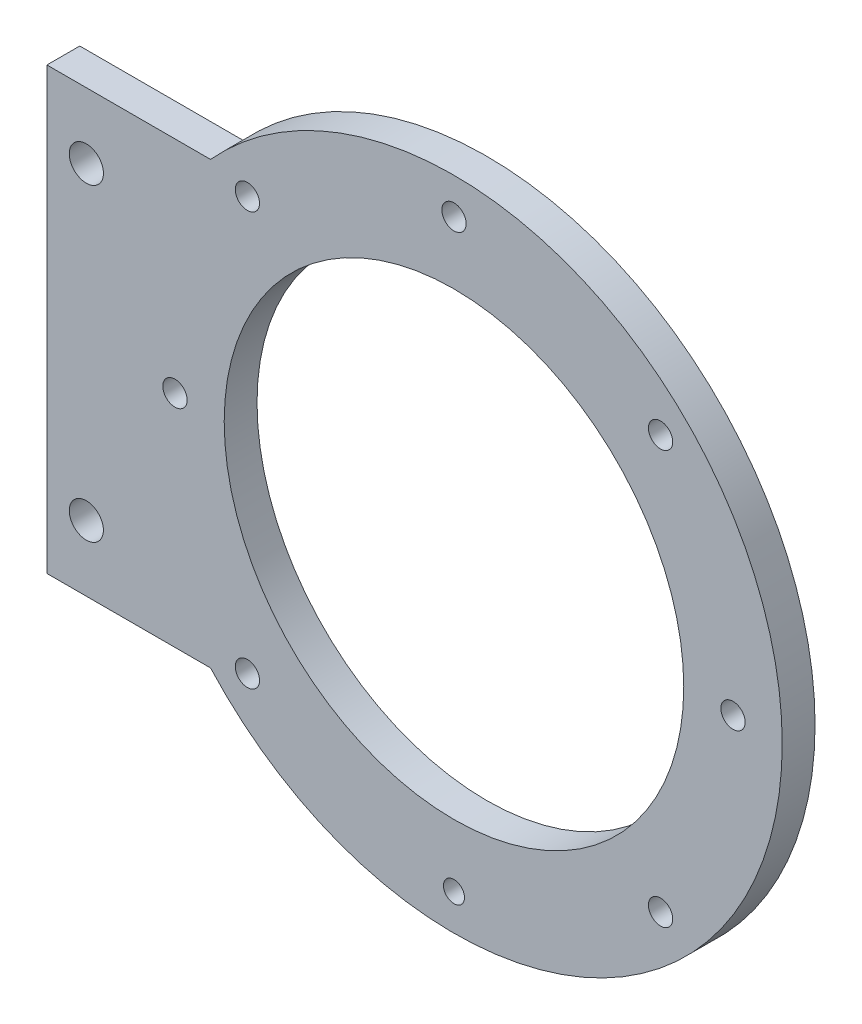
SolidWorks part; units mm, degrees
ref_plane "前视基准面" through (0, 0, 0) normal (0, 0, 1) x (1, 0, 0)
ref_plane "上视基准面" through (0, 0, 0) normal (0, 1, 0) x (1, 0, 0)
ref_plane "右视基准面" through (0, 0, 0) normal (1, 0, 0) x (0, 0, -1)
other "Configuration Table"
sketch "草图1" plane through (0, 0, 0) normal (0, 0, 1) x (1, 0, 0)
  line L0 (0, -67.082) -> (0, 0)
  line L1 (0, -67.082) -> (-12, -67.082)
  line L2 (-12, -67.082) -> (-12, 0)
  line L3 (0, 0) -> (-12, 0)
  line L4 (-12, -33.541) -> (95.5454, -33.541) construction
  line L5 (0, 0) -> (20, 0)
  line L6 (0, 0) -> (0, -67.082)
  line L7 (0, -67.082) -> (20, -67.082)
  line L8 (20, 0) -> (20, -67.082)
  circle A0 centre (-6, -57.082) radius 2.6
  circle A1 centre (-6, -10) radius 2.6
  circle A2 centre (50, -33.541) radius 50
  dimension "D1" = 5.2
  dimension "D2" = 6
  dimension "D5" = 6
  dimension "D6" = 10
  dimension "D8" = 6
  dimension "D9" = 5.2
  dimension "D10" = 10
  dimension "D12" = 100
  dimension "D3" = 12
  dimension "D4" = 67.082
  dimension "D7" = 12
  dimension "D11" = 20
  dimension "D13" = 50
extrude "凸台-拉伸1" add sketch "草图1" along normal blind 5
sketch "草图2" plane through (0, 0, 5) normal (0, 0, 1) x (1, 0, 0)
  line L3 (12.919, 0) -> (-12, 0)
  line L4 (-12, 0) -> (-12, -67.082)
  line L5 (-12, -67.082) -> (12.919, -67.082)
  line L6 (12.919, 0) -> (-12, 0)
  line L7 (-12, 0) -> (-12, -67.082)
  line L8 (-12, -67.082) -> (12.919, -67.082)
  arc A1 (12.919, -67.082) -> (12.919, 0) centre (50, -33.541) ccw
  arc A2 (12.919, -67.082) -> (12.919, 0) centre (50, -33.541) ccw
  circle A5 centre (92.5, -33.541) radius 1.85
  circle A16 centre (80.052, -63.5931) radius 1.85
  circle A17 centre (50, -76.041) radius 1.85
  circle A18 centre (19.948, -63.5931) radius 1.85
  circle A19 centre (7.5, -33.541) radius 1.85
  circle A20 centre (19.948, -3.489) radius 1.85
  circle A21 centre (50, 8.959) radius 1.85
  circle A22 centre (80.052, -3.489) radius 1.85
  point P18 (50, -33.541)
  point P25 (50, -33.541)
  dimension "D2" = 8
  dimension "D6" = 3.7
  dimension "D5" = 42.5
  dimension "D1" = 0
extrude "切除-拉伸1" cut sketch "草图2" against normal through all
sketch "草图3" plane through (0, 0, 5) normal (0, 0, 1) x (1, 0, 0)
  line L3 (12.919, 0) -> (-12, 0)
  line L4 (-12, 0) -> (-12, -67.082)
  line L5 (-12, -67.082) -> (12.919, -67.082)
  line L6 (12.919, 0) -> (-12, 0)
  line L7 (-12, 0) -> (-12, -67.082)
  line L8 (-12, -67.082) -> (12.919, -67.082)
  circle A0 centre (50, -33.541) radius 35
  arc A1 (12.919, -67.082) -> (12.919, 0) centre (50, -33.541) ccw
  arc A2 (12.919, -67.082) -> (12.919, 0) centre (50, -33.541) ccw
  dimension "D2" = 70
  dimension "D1" = 0
extrude "切除-拉伸2" cut sketch "草图3" against normal through all contours A0
sketch "草图4" plane through (0, 0, 5) normal (0, 0, 1) x (1, 0, 0)
  line L3 (12.919, 0) -> (-12, 0)
  line L4 (-12, 0) -> (-12, -67.082)
  line L5 (-12, -67.082) -> (12.919, -67.082)
  line L6 (12.919, 0) -> (-12, 0)
  line L7 (-12, 0) -> (-12, -67.082)
  line L8 (-12, -67.082) -> (12.919, -67.082)
  circle A0 centre (50, 10.959) radius 1.85
  arc A1 (12.919, -67.082) -> (12.919, 0) centre (50, -33.541) ccw
  arc A2 (12.919, -67.082) -> (12.919, 0) centre (50, -33.541) ccw
  circle A3 centre (81.4663, -2.0748) radius 1.85
  circle A4 centre (50, -78.041) radius 1.6
  circle A5 centre (94.5, -33.541) radius 1.85
  circle A6 centre (81.4663, -65.0073) radius 1.85
  circle A7 centre (50, -78.041) radius 1.85
  circle A8 centre (18.5337, -65.0073) radius 1.85
  circle A9 centre (5.5, -33.541) radius 1.85
  circle A10 centre (18.5337, -2.0748) radius 1.85
  point P26 (50, -33.541)
  point P28 (50, -33.541)
  dimension "D2" = 3.7
  dimension "D4" = 3.2
  dimension "D5" = 44.5
  dimension "D3" = 44.5
  dimension "D1" = 0
  dimension "D6" = 8
extrude "切除-拉伸3" cut sketch "草图4" against normal blind 10 contours A0 | A4 | A10 | A3 | A8 | A6
sketch "草图5" plane through (0, 0, 5) normal (0, 0, 1) x (1, 0, 0)
  circle A1 centre (-6, -10) radius 2.6
  circle A2 centre (-6, -10) radius 2.6
  circle A3 centre (-6, -57.082) radius 2.6
  circle A4 centre (-6, -57.082) radius 2.6
  circle A5 centre (7.5, -33.541) radius 1.85
  circle A6 centre (7.5, -33.541) radius 1.85
  circle A7 centre (92.5, -33.541) radius 1.85
  circle A8 centre (92.5, -33.541) radius 1.85
  circle A9 centre (50, -33.541) radius 35
  circle A10 centre (50, -33.541) radius 35
  circle A11 centre (18.5337, -65.0073) radius 1.85
  circle A12 centre (18.5337, -65.0073) radius 1.85
  circle A13 centre (81.4663, -2.0748) radius 1.85
  circle A14 centre (81.4663, -2.0748) radius 1.85
  circle A15 centre (18.5337, -2.0748) radius 1.85
  circle A16 centre (18.5337, -2.0748) radius 1.85
  circle A17 centre (50, -78.041) radius 1.6
  circle A18 centre (50, -78.041) radius 1.6
  circle A19 centre (81.4663, -65.0073) radius 1.85
  circle A20 centre (81.4663, -65.0073) radius 1.85
  circle A21 centre (50, 10.959) radius 1.85
  circle A22 centre (50, 10.959) radius 1.85
  dimension "D1" = 0
  dimension "D2" = 0
  dimension "D3" = 0
  dimension "D4" = 0
  dimension "D5" = 0
  dimension "D6" = 0
  dimension "D7" = 0
  dimension "D8" = 0
  dimension "D9" = 0
  dimension "D10" = 0
  dimension "D11" = 0
move or copy body "实体-移动/复制1" [suppressed] bodies to move or copy 109 parameters "D1"=0, "D2"=0, "D3"=0
move or copy body "实体-移动/复制2" [suppressed] bodies to move or copy 110 parameters "D1"=0, "D2"=0, "D3"=0
move or copy body "实体-移动/复制3" [suppressed] bodies to move or copy 111 parameters "D1"=0, "D2"=0, "D3"=0
move or copy body "实体-移动/复制4" [suppressed] bodies to move or copy 112 parameters "D1"=0, "D2"=0, "D3"=0
